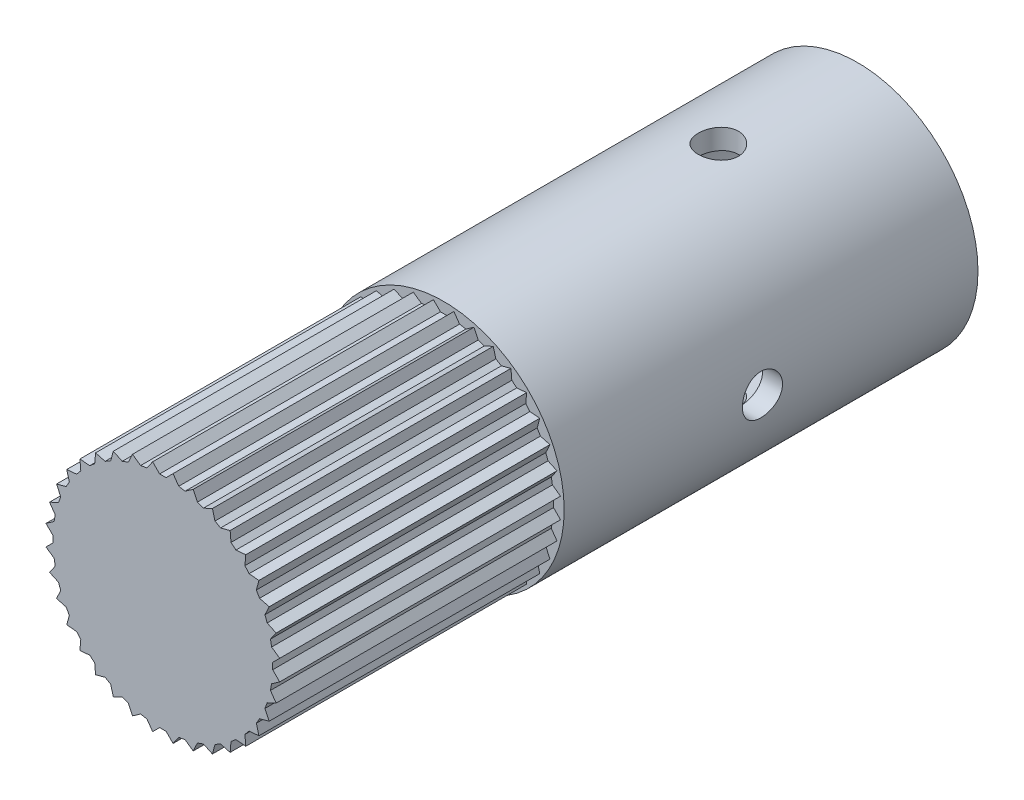
SolidWorks part; units mm, degrees
material "AISI 4130 Steel, annealed at 865C"
ref_plane "X-Y Datum" through (0, 0, 0) normal (0, 0, 1) x (1, 0, 0)
ref_plane "X-Z Datum" through (0, 0, 0) normal (0, 1, 0) x (1, 0, 0)
ref_plane "Y-Z Datum" through (0, 0, 0) normal (1, 0, 0) x (0, 0, -1)
sketch "Sketch9" plane through (0, 0, 0) normal (0, 1, 0) x (1, 0, 0)
  line L0 (16.002, 0) -> (0, 0)
  line L1 (0, 0) -> (0, -382.27)
  line L2 (0, -382.27) -> (-72.2493, -518.1512)
  dimension "D1" = 153.895
  dimension "D2" = 28
  dimension "D3" = 382.27
  dimension "D5" = 16.002
sketch "Sketch5" plane through (0, 0, 0) normal (0, 1, 0) x (1, 0, 0)
  line L0 (7.9375, -77.0661) -> (7.9375, -22.1615)
  line L1 (7.9375, -22.1615) -> (9.525, -22.1615)
  line L2 (9.525, -22.1615) -> (9.525, -77.0661)
  line L3 (9.525, -77.0661) -> (7.9375, -77.0661)
  line L5 (16.002, 0) -> (0, 0) construction
  line L6 (0, 0) -> (0, -382.27) construction
  line L7 (0, -382.27) -> (9.525, -382.27) construction
  line L8 (12.5602, -53.14) -> (0, -53.14) construction
  dimension "D1" = 1.5875
  dimension "D2" = 22.1615
  dimension "D3" = 7.9375
  dimension "D4" = 329.13
  dimension "D5" = 305.2039
revolve "Revolve2" add sketch "Sketch5" angle 360 about L1
sketch "Sketch6" plane through (0, 0, 0) normal (0, 1, 0) x (1, 0, 0)
  circle A0 centre (0, -33.1635) radius 1.5875 construction
  circle A1 centre (0, -33.1635) radius 1.5875
sketch "Sketch7" plane through (0, 0, 0) normal (1, 0, 0) x (0, 0, -1)
  circle A2 centre (-39.196, 0) radius 1.5875
  circle A4 centre (-39.196, 0) radius 1.5875 construction
extrude "Cut-Extrude5" cut sketch "Sketch7" against normal through all both and the other way through all
extrude "Cut-Extrude6" cut sketch "Sketch6" against normal through all both and the other way through all
sketch "Sketch8" plane through (0, 0, 0) normal (0, 0, 1) x (1, 0, 0)
  line L0 (9.2357, -0.808) -> (8.6817, -0.254)
  line L1 (8.6817, -0.254) -> (8.6817, 0.254)
  line L2 (8.6817, 0.254) -> (9.2357, 0.808)
  line L3 (8.6817, 0) -> (0, 0) construction
  line L4 (8.9551, -2.3995) -> (8.5057, -1.7577)
  line L5 (8.5057, -1.7577) -> (8.5939, -1.2574)
  line L6 (8.5939, -1.2574) -> (9.2357, -0.808)
  line L7 (8.4024, -3.9181) -> (8.0713, -3.208)
  line L8 (8.0713, -3.208) -> (8.245, -2.7306)
  line L9 (8.245, -2.7306) -> (8.9551, -2.3995)
  line L10 (7.5944, -5.3176) -> (7.3916, -4.5608)
  line L11 (7.3916, -4.5608) -> (7.6456, -4.1209)
  line L12 (7.6456, -4.1209) -> (8.4024, -3.9181)
  line L13 (6.5556, -6.5556) -> (6.4873, -5.7751)
  line L14 (6.4873, -5.7751) -> (6.8138, -5.3859)
  line L15 (6.8138, -5.3859) -> (7.5944, -5.3176)
  line L16 (5.3176, -7.5944) -> (5.3859, -6.8138)
  line L17 (5.3859, -6.8138) -> (5.7751, -6.4873)
  line L18 (5.7751, -6.4873) -> (6.5556, -6.5556)
  line L19 (3.9181, -8.4024) -> (4.1209, -7.6456)
  line L20 (4.1209, -7.6456) -> (4.5608, -7.3916)
  line L21 (4.5608, -7.3916) -> (5.3176, -7.5944)
  line L22 (2.3995, -8.9551) -> (2.7306, -8.245)
  line L23 (2.7306, -8.245) -> (3.208, -8.0713)
  line L24 (3.208, -8.0713) -> (3.9181, -8.4024)
  line L25 (0.808, -9.2357) -> (1.2574, -8.5939)
  line L26 (1.2574, -8.5939) -> (1.7577, -8.5057)
  line L27 (1.7577, -8.5057) -> (2.3995, -8.9551)
  line L28 (-0.808, -9.2357) -> (-0.254, -8.6817)
  line L29 (-0.254, -8.6817) -> (0.254, -8.6817)
  line L30 (0.254, -8.6817) -> (0.808, -9.2357)
  line L31 (-2.3995, -8.9551) -> (-1.7577, -8.5057)
  line L32 (-1.7577, -8.5057) -> (-1.2574, -8.5939)
  line L33 (-1.2574, -8.5939) -> (-0.808, -9.2357)
  line L34 (-3.9181, -8.4024) -> (-3.208, -8.0713)
  line L35 (-3.208, -8.0713) -> (-2.7306, -8.245)
  line L36 (-2.7306, -8.245) -> (-2.3995, -8.9551)
  line L37 (-5.3176, -7.5944) -> (-4.5608, -7.3916)
  line L38 (-4.5608, -7.3916) -> (-4.1209, -7.6456)
  line L39 (-4.1209, -7.6456) -> (-3.9181, -8.4024)
  line L40 (-6.5556, -6.5556) -> (-5.7751, -6.4873)
  line L41 (-5.7751, -6.4873) -> (-5.3859, -6.8138)
  line L42 (-5.3859, -6.8138) -> (-5.3176, -7.5944)
  line L43 (-7.5944, -5.3176) -> (-6.8138, -5.3859)
  line L44 (-6.8138, -5.3859) -> (-6.4873, -5.7751)
  line L45 (-6.4873, -5.7751) -> (-6.5556, -6.5556)
  line L46 (-8.4024, -3.9181) -> (-7.6456, -4.1209)
  line L47 (-7.6456, -4.1209) -> (-7.3916, -4.5608)
  line L48 (-7.3916, -4.5608) -> (-7.5944, -5.3176)
  line L49 (-8.9551, -2.3995) -> (-8.245, -2.7306)
  line L50 (-8.245, -2.7306) -> (-8.0713, -3.208)
  line L51 (-8.0713, -3.208) -> (-8.4024, -3.9181)
  line L52 (-9.2357, -0.808) -> (-8.5939, -1.2574)
  line L53 (-8.5939, -1.2574) -> (-8.5057, -1.7577)
  line L54 (-8.5057, -1.7577) -> (-8.9551, -2.3995)
  line L55 (-9.2357, 0.808) -> (-8.6817, 0.254)
  line L56 (-8.6817, 0.254) -> (-8.6817, -0.254)
  line L57 (-8.6817, -0.254) -> (-9.2357, -0.808)
  line L58 (-8.9551, 2.3995) -> (-8.5057, 1.7577)
  line L59 (-8.5057, 1.7577) -> (-8.5939, 1.2574)
  line L60 (-8.5939, 1.2574) -> (-9.2357, 0.808)
  line L61 (-8.4024, 3.9181) -> (-8.0713, 3.208)
  line L62 (-8.0713, 3.208) -> (-8.245, 2.7306)
  line L63 (-8.245, 2.7306) -> (-8.9551, 2.3995)
  line L64 (-7.5944, 5.3176) -> (-7.3916, 4.5608)
  line L65 (-7.3916, 4.5608) -> (-7.6456, 4.1209)
  line L66 (-7.6456, 4.1209) -> (-8.4024, 3.9181)
  line L67 (-6.5556, 6.5556) -> (-6.4873, 5.7751)
  line L68 (-6.4873, 5.7751) -> (-6.8138, 5.3859)
  line L69 (-6.8138, 5.3859) -> (-7.5944, 5.3176)
  line L70 (-5.3176, 7.5944) -> (-5.3859, 6.8138)
  line L71 (-5.3859, 6.8138) -> (-5.7751, 6.4873)
  line L72 (-5.7751, 6.4873) -> (-6.5556, 6.5556)
  line L73 (-3.9181, 8.4024) -> (-4.1209, 7.6456)
  line L74 (-4.1209, 7.6456) -> (-4.5608, 7.3916)
  line L75 (-4.5608, 7.3916) -> (-5.3176, 7.5944)
  line L76 (-2.3995, 8.9551) -> (-2.7306, 8.245)
  line L77 (-2.7306, 8.245) -> (-3.208, 8.0713)
  line L78 (-3.208, 8.0713) -> (-3.9181, 8.4024)
  line L79 (-0.808, 9.2357) -> (-1.2574, 8.5939)
  line L80 (-1.2574, 8.5939) -> (-1.7577, 8.5057)
  line L81 (-1.7577, 8.5057) -> (-2.3995, 8.9551)
  line L82 (0.808, 9.2357) -> (0.254, 8.6817)
  line L83 (0.254, 8.6817) -> (-0.254, 8.6817)
  line L84 (-0.254, 8.6817) -> (-0.808, 9.2357)
  line L85 (2.3995, 8.9551) -> (1.7577, 8.5057)
  line L86 (1.7577, 8.5057) -> (1.2574, 8.5939)
  line L87 (1.2574, 8.5939) -> (0.808, 9.2357)
  line L88 (3.9181, 8.4024) -> (3.208, 8.0713)
  line L89 (3.208, 8.0713) -> (2.7306, 8.245)
  line L90 (2.7306, 8.245) -> (2.3995, 8.9551)
  line L91 (5.3176, 7.5944) -> (4.5608, 7.3916)
  line L92 (4.5608, 7.3916) -> (4.1209, 7.6456)
  line L93 (4.1209, 7.6456) -> (3.9181, 8.4024)
  line L94 (6.5556, 6.5556) -> (5.7751, 6.4873)
  line L95 (5.7751, 6.4873) -> (5.3859, 6.8138)
  line L96 (5.3859, 6.8138) -> (5.3176, 7.5944)
  line L97 (7.5944, 5.3176) -> (6.8138, 5.3859)
  line L98 (6.8138, 5.3859) -> (6.4873, 5.7751)
  line L99 (6.4873, 5.7751) -> (6.5556, 6.5556)
  line L100 (8.4024, 3.9181) -> (7.6456, 4.1209)
  line L101 (7.6456, 4.1209) -> (7.3916, 4.5608)
  line L102 (7.3916, 4.5608) -> (7.5944, 5.3176)
  line L103 (8.9551, 2.3995) -> (8.245, 2.7306)
  line L104 (8.245, 2.7306) -> (8.0713, 3.208)
  line L105 (8.0713, 3.208) -> (8.4024, 3.9181)
  line L106 (9.2357, 0.808) -> (8.5939, 1.2574)
  line L107 (8.5939, 1.2574) -> (8.5057, 1.7577)
  line L108 (8.5057, 1.7577) -> (8.9551, 2.3995)
  circle A0 centre (0, 0) radius 12.7
  circle A1 centre (0, 0) radius 9.271 construction
  circle A2 centre (0, 0) radius 8.6854 construction
  point P153 (0, 0)
  dimension "D1" = 25.4
  dimension "D4" = 18.542
  dimension "D6" = 17.3708
  dimension "D2" = 0.508
  dimension "D3" = 135
  dimension "D5" = 36
ref_plane "Plane1" through (0, 0, 47.5615) normal (0, 0, -1) x (-1, 0, 0)
sketch "Sketch10" plane through (0, 0, 47.5615) normal (0, 0, -1) x (-1, 0, 0)
  circle A0 centre (0, 0) radius 7.9375
  dimension "D1" = 15.875
extrude "Boss-Extrude1" add sketch "Sketch10" against normal up to surface (29.5046 mm away) up to face at (-9.525, 0, 77.0661)
sketch "Sketch11" plane through (0, 0, 22.1615) normal (0, 0, -1) x (-1, 0, 0)
  line L0 (0, 9.525) -> (13.3548, 9.525) construction
  line L1 (0, 9.525) -> (0, 15.4312) construction
  line L2 (-9.525, 0) -> (-9.525, 9.1744) construction
  line L3 (-9.525, 0) -> (-16.674, 0) construction
  circle A0 centre (0, 0) radius 9.525 construction
  point P0 (0, 9.525)
  point P1 (-9.525, 0)
extrude "Cut-Extrude7" cut sketch "Sketch8" along normal blind 25.4 from offset 54.8691
